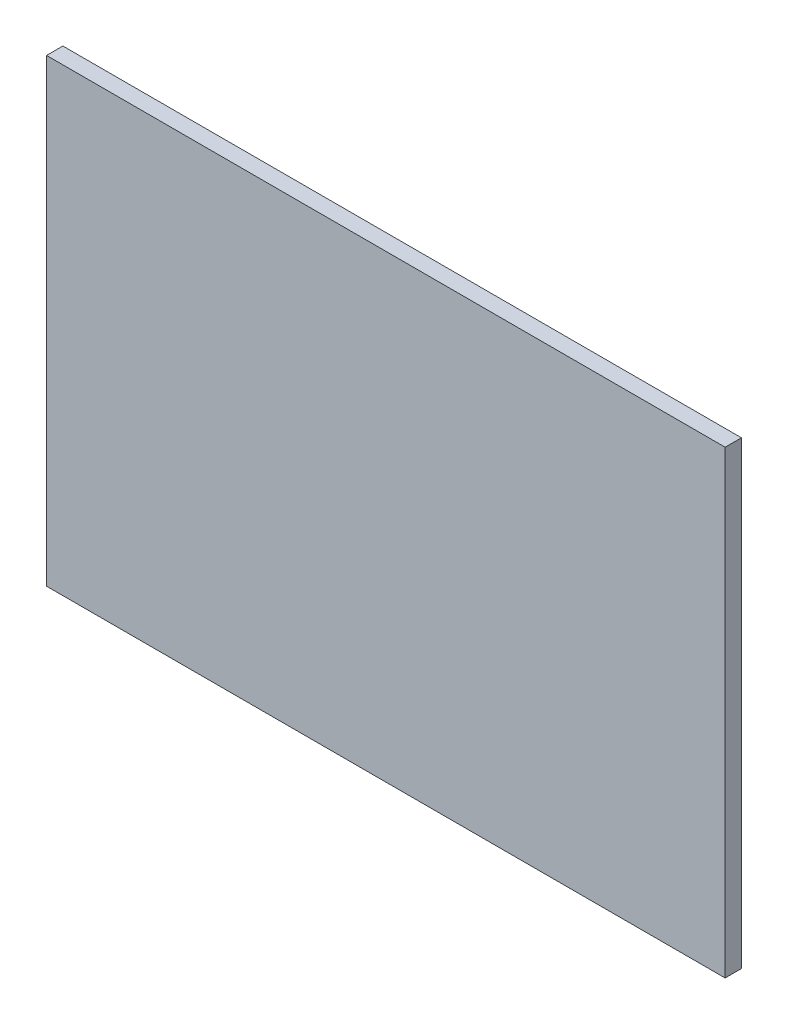
SolidWorks part; units mm, degrees
ref_plane "前基準面" through (0, 0, 0) normal (0, 0, 1) x (1, 0, 0)
ref_plane "上基準面" through (0, 0, 0) normal (0, 1, 0) x (1, 0, 0)
ref_plane "右基準面" through (0, 0, 0) normal (1, 0, 0) x (0, 0, -1)
sketch "草圖1" plane through (0, 0, 0) normal (0, 0, 1) x (1, 0, 0)
  line L1 (0, 0) -> (124, 0)
  line L2 (0, 0) -> (0, -84)
  line L3 (0, -84) -> (124, -84)
  line L4 (124, 0) -> (124, -84)
  dimension "D1" = 84
  dimension "D2" = 124
extrude "填料-伸長1" add sketch "草圖1" along normal blind 2.98
